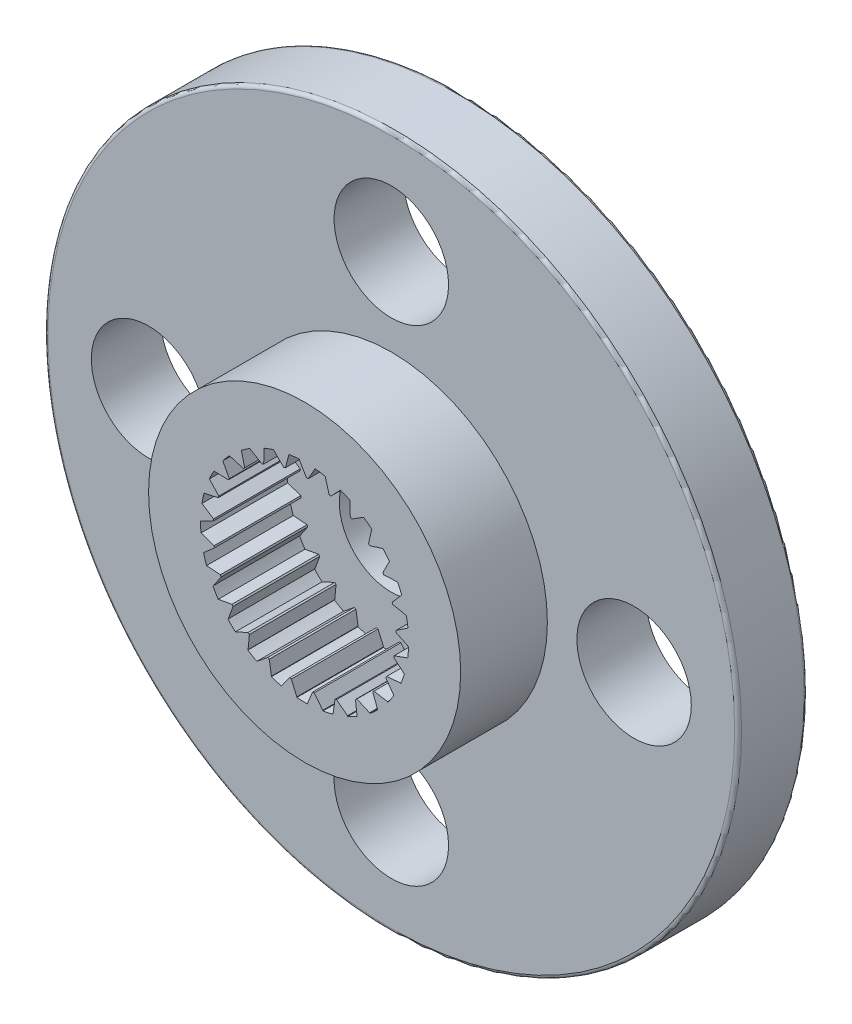
SolidWorks part; units mm, degrees
material "PVC 0.007 Plasticized"
ref_plane "Front Plane" through (0, 0, 0) normal (0, 0, 1) x (1, 0, 0)
ref_plane "Top Plane" through (0, 0, 0) normal (0, 1, 0) x (1, 0, 0)
ref_plane "Right Plane" through (0, 0, 0) normal (1, 0, 0) x (0, 0, -1)
sketch "Sketch3" plane through (0, 0, 0) normal (0, 0, 1) x (1, 0, 0)
  circle A2 centre (0, 0) radius 10
  circle A3 centre (-3.75, 7.75) radius 0.75 construction
  circle A15 centre (-7.75, 3.75) radius 0.75 construction
  circle A16 centre (-7.75, 0) radius 0.75 construction
  circle A17 centre (-7.75, -3.75) radius 0.75 construction
  circle A18 centre (-3.75, -7.75) radius 0.75 construction
  circle A19 centre (0, -7.75) radius 0.75 construction
  circle A20 centre (3.75, -7.75) radius 0.75 construction
  circle A21 centre (7.75, -3.75) radius 0.75 construction
  circle A22 centre (7.75, 0) radius 0.75 construction
  circle A23 centre (7.75, 3.75) radius 0.75 construction
  circle A24 centre (3.75, 7.75) radius 0.75 construction
  circle A25 centre (0, 7.75) radius 0.75 construction
  circle A28 centre (0, 0) radius 1.5
  dimension "D1" = 3
  dimension "D2" = 1.5
  dimension "D3" = 7.5
  dimension "D4" = 20
  dimension "D6" = 3.75
  dimension "D10" = 3.75
  dimension "D11" = 3.75
  dimension "D12" = 15.5
  dimension "D13" = 15.5
  dimension "D5" = 3.75
  dimension "D7" = 7.75
  dimension "D8" = 4
  dimension "D9" = 4
extrude "Boss-Extrude2" add sketch "Sketch3" along normal blind 2 separate body
fillet "Fillet1" radius 0.1 2 edges at (10, 0, 2) (10, 0, 0)
sketch "Sketch5" plane through (0, 0, 2) normal (0, 0, 1) x (1, 0, 0)
  circle A0 centre (0, 0) radius 4.5
  circle A1 centre (0, 0) radius 3
  dimension "D1" = 9
  dimension "D2" = 6
extrude "Boss-Extrude3" add sketch "Sketch5" along normal blind 2.5
sketch "Sketch6" plane through (0, 0, 0) normal (0, 0, -1) x (-1, 0, 0)
  circle A0 centre (0, 0) radius 4.5
  circle A1 centre (0, 0) radius 3.5
  dimension "D1" = 7
  dimension "D2" = 9
extrude "Cut-Extrude3" cut sketch "Sketch6" against normal blind 0.3
sketch "Sketch2" plane through (0, 0, 0) normal (0, 0, 1) x (1, 0, 0)
  line L0 (-0.6719, -2.9238) -> (-0.2249, -2.9756) construction
  line L1 (-0.6719, -2.9238) -> (-0.0143, -3) construction
  line L2 (-0.2249, -2.9756) -> (-0.2249, -3.0547)
  line L3 (-0.6719, -2.9238) -> (-0.4334, -2.6027)
  line L4 (-0.4334, -2.6027) -> (-0.3837, -2.6084)
  line L5 (-0.3837, -2.6084) -> (-0.2249, -2.9756)
  line L6 (-0.2249, -3.0547) -> (-0.6719, -3.0328)
  line L7 (-0.6719, -3.0328) -> (-0.6719, -2.9238)
  circle A2 centre (0, 0) radius 3 construction
  dimension "D1" = 0.45
  dimension "D2" = 3.809
  dimension "D3" = 0.109
  dimension "D5" = 0.05
  dimension "D6" = 120
  dimension "D8" = 120
extrude "Boss-Extrude1" add sketch "Sketch2" along normal up to surface (4.5 mm away) up to face at (4.5, 0, 4.5)
pattern_circular "CirPattern6" count 25 over 360 about axis through (0, 0, 0) along (0, 0, 1) of "Boss-Extrude1"
sketch "Sketch8" plane through (0, 0, 2) normal (0, 0, 1) x (1, 0, 0)
  line L0 (-9.9, 0) -> (9.9, 0) construction
  line L2 (0, -9.9) -> (0, 10) construction
  circle A0 centre (0, 7) radius 1.65
  circle A1 centre (0, 0) radius 9.9 construction
  circle A2 centre (0, 0) radius 10 construction
  circle A3 centre (0, -7) radius 1.65
  circle A4 centre (7, 0) radius 1.65
  circle A5 centre (-7, 0) radius 1.65
  dimension "D1" = 3.3
  dimension "D2" = 14
  dimension "D3" = 14
extrude "Cut-Extrude4" cut sketch "Sketch8" against normal up to next
